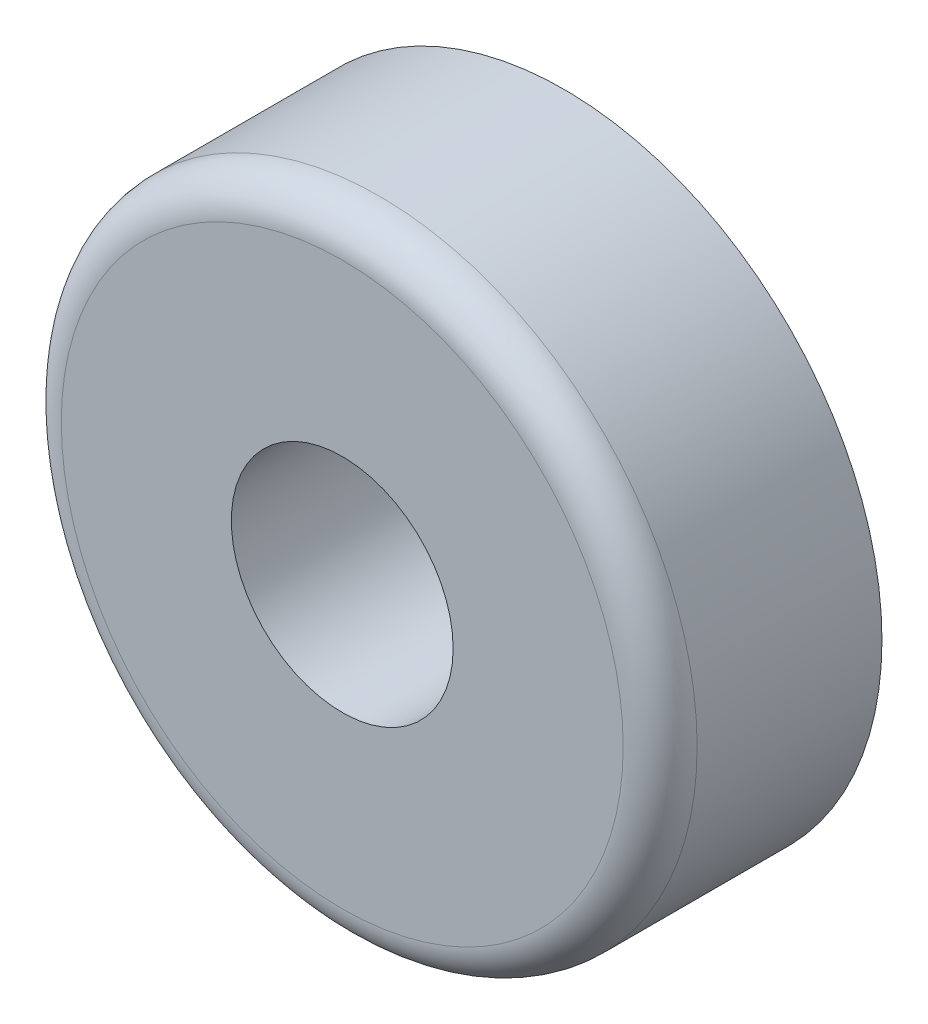
SolidWorks part; units mm, degrees
ref_plane "Front Plane" through (0, 0, 0) normal (0, 0, 1) x (1, 0, 0)
ref_plane "Top Plane" through (0, 0, 0) normal (0, 1, 0) x (1, 0, 0)
ref_plane "Right Plane" through (0, 0, 0) normal (1, 0, 0) x (0, 0, -1)
sketch "Sketch1" plane through (0, 0, 0) normal (0, 0, 1) x (1, 0, 0)
  circle A0 centre (0, 0) radius 1.5
  circle A1 centre (0, 0) radius 4.3
  dimension "D1" = 3
  dimension "D2" = 8.6
extrude "Boss-Extrude1" add sketch "Sketch1" along normal blind 3
fillet "Fillet1" radius 0.5 1 edges at (4.3, 0, 3)
